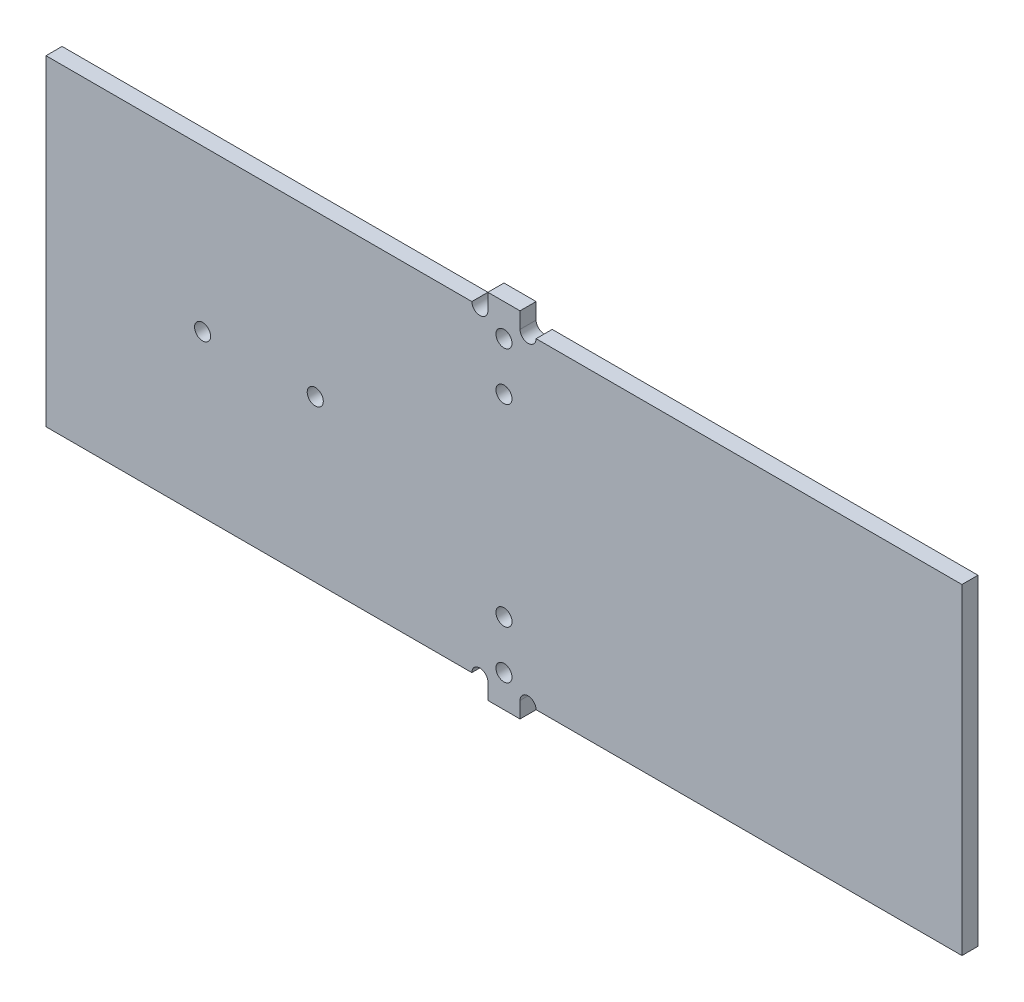
SolidWorks part; units mm, degrees
material "自訂玻璃纖維"
ref_plane "前基準面" through (0, 0, 0) normal (0, 0, 1) x (1, 0, 0)
ref_plane "上基準面" through (0, 0, 0) normal (0, 1, 0) x (1, 0, 0)
ref_plane "右基準面" through (0, 0, 0) normal (1, 0, 0) x (0, 0, -1)
sketch "草圖1" plane through (0, 0, 0) normal (0, 0, 1) x (1, 0, 0)
  line L0 (5.3395, 31.8944) -> (57.3395, 31.8944)
  line L1 (-54.6605, 31.8944) -> (-2.6605, 31.8944)
  line L2 (-55.6605, 30.8944) -> (-55.6605, -7.1056)
  line L3 (-54.6605, -8.1056) -> (-2.6605, -8.1056)
  line L4 (58.3395, 30.8944) -> (58.3395, -7.1056)
  line L5 (5.3395, -8.1056) -> (57.3395, -8.1056)
  line L6 (-0.6605, 31.8944) -> (-0.6605, 33.8944)
  line L7 (-0.6605, 33.8944) -> (3.3395, 33.8944)
  line L8 (3.3395, 31.8944) -> (3.3395, 33.8944)
  line L9 (3.3395, -8.1056) -> (3.3395, -10.1056)
  line L10 (-0.6605, -10.1056) -> (3.3395, -10.1056)
  line L11 (-0.6605, -8.1056) -> (-0.6605, -10.1056)
  line L12 (-55.6605, 30.8944) -> (-55.6605, 31.8944)
  line L13 (-55.6605, 31.8944) -> (-54.6605, 31.8944)
  line L14 (-55.6605, -7.1056) -> (-55.6605, -8.1056)
  line L15 (-55.6605, -8.1056) -> (-54.6605, -8.1056)
  line L16 (57.3395, 31.8944) -> (58.3395, 31.8944)
  line L17 (58.3395, 31.8944) -> (58.3395, 30.8944)
  line L18 (58.3395, -7.1056) -> (58.3395, -8.1056)
  line L19 (58.3395, -8.1056) -> (57.3395, -8.1056)
  circle A0 centre (1.3395, -6.1056) radius 1
  circle A1 centre (1.3395, 29.8944) radius 1
  arc A6 (-0.6605, 31.8944) -> (-2.6605, 31.8944) centre (-1.6605, 31.8944) cw
  arc A7 (3.3395, 31.8944) -> (5.3395, 31.8944) centre (4.3395, 31.8944) ccw
  arc A8 (3.3395, -8.1056) -> (5.3395, -8.1056) centre (4.3395, -8.1056) cw
  arc A9 (-0.6605, -8.1056) -> (-2.6605, -8.1056) centre (-1.6605, -8.1056) ccw
  point P12 (58.3395, 31.8944)
  point P15 (-55.6605, -8.1056)
  point P18 (-55.6605, 31.8944)
  dimension "D3" = 4
  dimension "D4" = 2
  dimension "D5" = 2
  dimension "D1" = 114
  dimension "D2" = 40
extrude "填料-伸長1" add sketch "草圖1" along normal blind 2
sketch "草圖2" plane through (0, 0, 2) normal (0, 0, 1) x (1, 0, 0)
  line L0 (-2.6605, 31.8944) -> (-55.6605, 31.8944) construction
  circle A0 centre (1.3395, 23.8944) radius 1
  circle A1 centre (1.3395, -0.1056) radius 1
  circle A2 centre (-36.1721, 11.8944) radius 1
  circle A3 centre (-22.1488, 11.8944) radius 1
  point P10 (-29.1605, 31.8944)
  dimension "D1" = 24
  dimension "D2" = 8
  dimension "D3" = 20
  dimension "D4" = 20
  dimension "D5" = 14.0233
  dimension "D6" = 7.0116
  dimension "D7" = 2
  dimension "D8" = 2
extrude "除料-伸長1" cut sketch "草圖2" against normal blind 2
